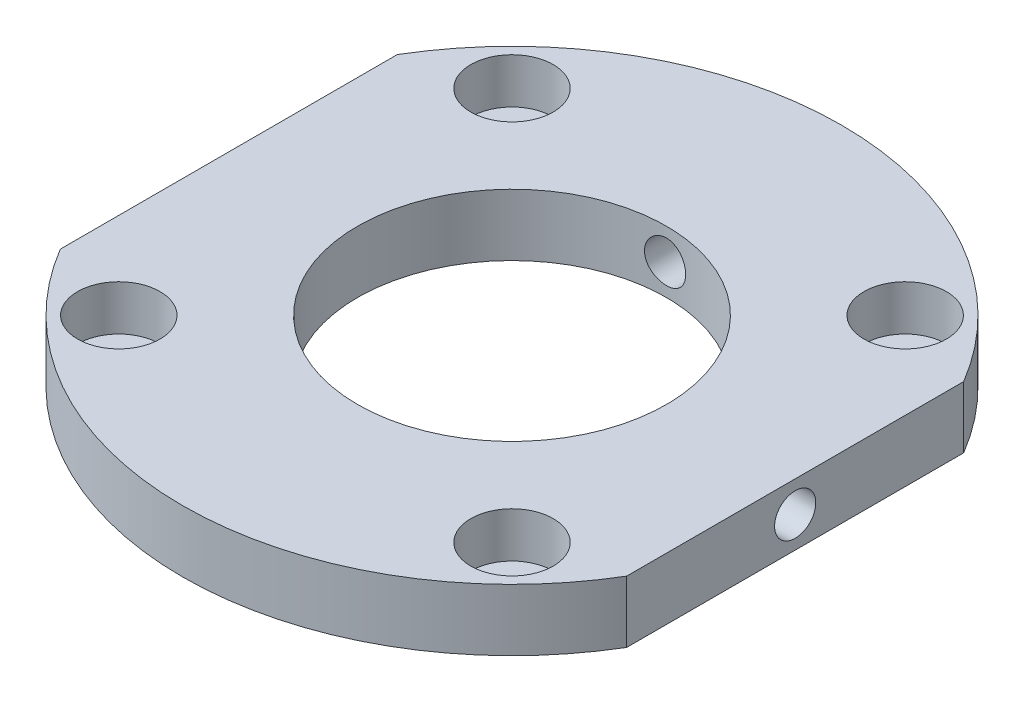
SolidWorks part; units mm, degrees
material "6061 Alloy"
ref_plane "Front Plane" through (0, 0, 0) normal (0, 0, 1) x (1, 0, 0)
ref_plane "Top Plane" through (0, 0, 0) normal (0, 1, 0) x (1, 0, 0)
ref_plane "Right Plane" through (0, 0, 0) normal (1, 0, 0) x (0, 0, -1)
sketch "Sketch1" plane through (0, 0, 0) normal (0, 1, 0) x (1, 0, 0)
  circle A0 centre (0, 0) radius 15
  circle A1 centre (0, 0) radius 32
  dimension "D1" = 30
  dimension "D2" = 64
extrude "Boss-Extrude1" add sketch "Sketch1" along normal blind 6
hole_wizard "CBORE for M4 Hex Socket Head Cap Screw2" positions "Sketch3" profile "Sketch5" counterbore size "M4" standard "DIN"
sketch "Sketch3" plane through (0, 6, 0) normal (0, 1, 0) x (1, 0, 0)
  line L0 (0, 0) -> (19.0919, 19.0919) construction
  line L2 (0, 0) -> (0, 6.5819) construction
  circle A0 centre (0, 0) radius 22
  point P2 (19.0919, 19.0919)
  point P9 (19.0919, -19.0919)
  point P10 (-19.0919, -19.0919)
  point P11 (-19.0919, 19.0919)
  dimension "D3" = 44
  dimension "D4" = 27
  dimension "D5" = 45
  dimension "D1" = 4
sketch "Sketch5" plane through (19.0919, 6, -19.0919) normal (1, 0, 0) x (0, 0, 1)
  line L0 (0, 0) -> (0, 13.2319)
  line L1 (0, 13.2319) -> (2.15, 11.94)
  line L2 (2.15, 11.94) -> (2.15, 4.4)
  line L3 (2.15, 4.4) -> (4, 4.4)
  line L4 (4, 4.4) -> (4, 0)
  line L5 (4, 0) -> (0, 0)
  line L10 (0, 13.2319) -> (-2.15, 11.94) construction
  line L11 (0, -6.35) -> (0, 107.95) construction
  dimension "Hole Dia." = 4.3
  dimension "Hole Depth" = 11.94
  dimension "C'Bore Dia." = 8
  dimension "C'Bore Depth" = 4.4
  dimension "Drill Angle" = 118
sketch "Sketch7" plane through (0, 0, 0) normal (1, 0, 0) x (0, 0, -1)
  line L0 (0, 0) -> (0, 6) construction
  line L1 (32, 6) -> (-32, 6) construction
  circle A0 centre (0, 3) radius 2
  dimension "D2" = 4
  dimension "D1" = 3
  dimension "D3" = 6
extrude "Cut-Extrude1" cut sketch "Sketch7" along normal blind 44.5
sketch "Sketch8" plane through (0, 0, 0) normal (0, 0, 1) x (1, 0, 0)
  line L0 (0, 0) -> (0, 6) construction
  line L1 (15, 6) -> (-15, 6) construction
  circle A0 centre (0, 3) radius 2
  dimension "D1" = 4
extrude "Cut-Extrude2" cut sketch "Sketch8" against normal blind 44.5
sketch "Sketch9" plane through (0, 6, 0) normal (0, 1, 0) x (1, 0, 0)
  line L0 (-27.5, 16.3631) -> (-27.5, -16.3631)
  line L1 (27.5, -16.3631) -> (27.5, 16.3631)
  line L2 (0, 0) -> (-27.5, 0) construction
  line L3 (0, 0) -> (27.5, 0) construction
  arc A0 (27.5, -16.3631) -> (27.5, 16.3631) centre (0, 0) ccw
  arc A1 (-27.5, 16.3631) -> (-27.5, -16.3631) centre (0, 0) ccw
  circle A2 centre (0, 0) radius 32 construction
  dimension "D1" = 55
extrude "Cut-Extrude3" cut sketch "Sketch9" against normal blind 10
equation "\"D1@Sketch7\"=\"D3@Sketch7\"/2"
